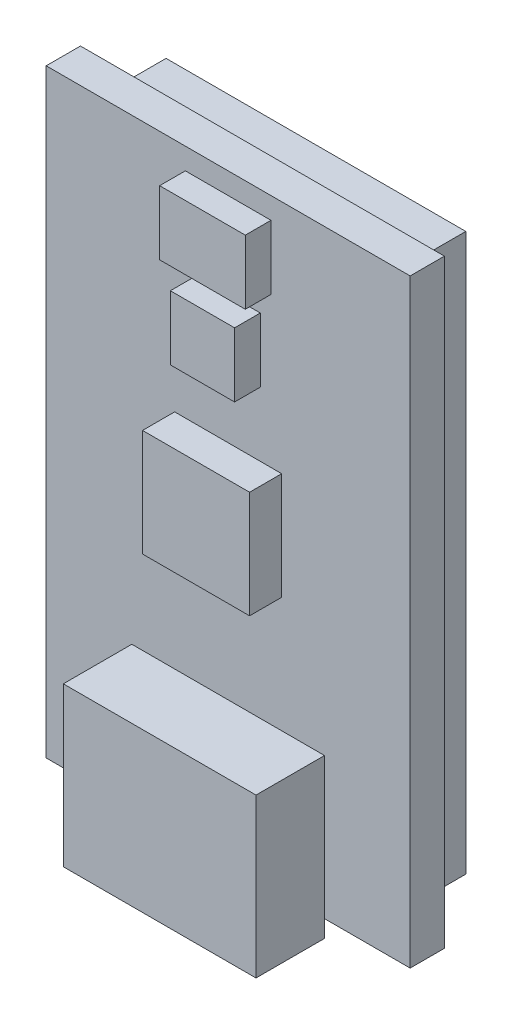
SolidWorks part; units mm, degrees
ref_plane "Front Plane" through (0, 0, 0) normal (0, 0, 1) x (1, 0, 0)
ref_plane "Top Plane" through (0, 0, 0) normal (0, 1, 0) x (1, 0, 0)
ref_plane "Right Plane" through (0, 0, 0) normal (1, 0, 0) x (0, 0, -1)
ref_plane "Plane1" through (0, 0, 10.6) normal (0, 0, 1) x (1, 0, 0)
sketch "Sketch1" plane through (0, 0, 10.6) normal (0, 0, 1) x (1, 0, 0)
  line L1 (11, 23) -> (25, 23)
  line L2 (11, 23) -> (11, 49)
  line L3 (11, 49) -> (25, 49)
  line L4 (25, 23) -> (25, 49)
  line L5 (11, 23) -> (25, 49) construction
  line L6 (11, 49) -> (25, 23) construction
  point P0 (18, 36)
extrude "Boss-Extrude1" add sketch "Sketch1" along normal blind 2.5
ref_plane "Plane2" through (0, 0, 13.1) normal (0, 0, 1) x (1, 0, 0)
sketch "Sketch2" plane through (0, 0, 13.1) normal (0, 0, 1) x (1, 0, 0)
  line L1 (9.5, 22) -> (26.5, 22)
  line L2 (9.5, 22) -> (9.5, 50)
  line L3 (9.5, 50) -> (26.5, 50)
  line L4 (26.5, 22) -> (26.5, 50)
  line L5 (9.5, 22) -> (26.5, 50) construction
  line L6 (9.5, 50) -> (26.5, 22) construction
  point P0 (18, 36)
extrude "Boss-Extrude2" add sketch "Sketch2" along normal blind 1.6
ref_plane "Plane3" through (0, 0, 14.7) normal (0, 0, 1) x (1, 0, 0)
sketch "Sketch3" plane through (0, 0, 14.7) normal (0, 0, 1) x (1, 0, 0)
  line L1 (13.5, 21.2) -> (22.5, 21.2)
  line L2 (13.5, 21.2) -> (13.5, 28.6)
  line L3 (13.5, 28.6) -> (22.5, 28.6)
  line L4 (22.5, 21.2) -> (22.5, 28.6)
  line L5 (13.5, 21.2) -> (22.5, 28.6) construction
  line L6 (13.5, 28.6) -> (22.5, 21.2) construction
  point P0 (18, 24.9)
extrude "Boss-Extrude3" add sketch "Sketch3" along normal blind 3.2
sketch "Sketch4" plane through (0, 0, 14.7) normal (0, 0, 1) x (1, 0, 0)
  line L1 (15.5, 34) -> (20.5, 34)
  line L2 (15.5, 34) -> (15.5, 39)
  line L3 (15.5, 39) -> (20.5, 39)
  line L4 (20.5, 34) -> (20.5, 39)
  line L5 (15.5, 34) -> (20.5, 39) construction
  line L6 (15.5, 39) -> (20.5, 34) construction
  point P0 (18, 36.5)
extrude "Boss-Extrude4" add sketch "Sketch4" along normal blind 1.5
sketch "Sketch5" plane through (0, 0, 14.7) normal (0, 0, 1) x (1, 0, 0)
  line L1 (16.5, 42) -> (19.5, 42)
  line L2 (16.5, 42) -> (16.5, 45)
  line L3 (16.5, 45) -> (19.5, 45)
  line L4 (19.5, 42) -> (19.5, 45)
  line L5 (16.5, 42) -> (19.5, 45) construction
  line L6 (16.5, 45) -> (19.5, 42) construction
  point P0 (18, 43.5)
extrude "Boss-Extrude5" add sketch "Sketch5" along normal blind 1.2
sketch "Sketch6" plane through (0, 0, 14.7) normal (0, 0, 1) x (1, 0, 0)
  line L1 (16, 46) -> (20, 46)
  line L2 (16, 46) -> (16, 49)
  line L3 (16, 49) -> (20, 49)
  line L4 (20, 46) -> (20, 49)
  line L5 (16, 46) -> (20, 49) construction
  line L6 (16, 49) -> (20, 46) construction
  point P0 (18, 47.5)
extrude "Boss-Extrude6" add sketch "Sketch6" along normal blind 1.2
